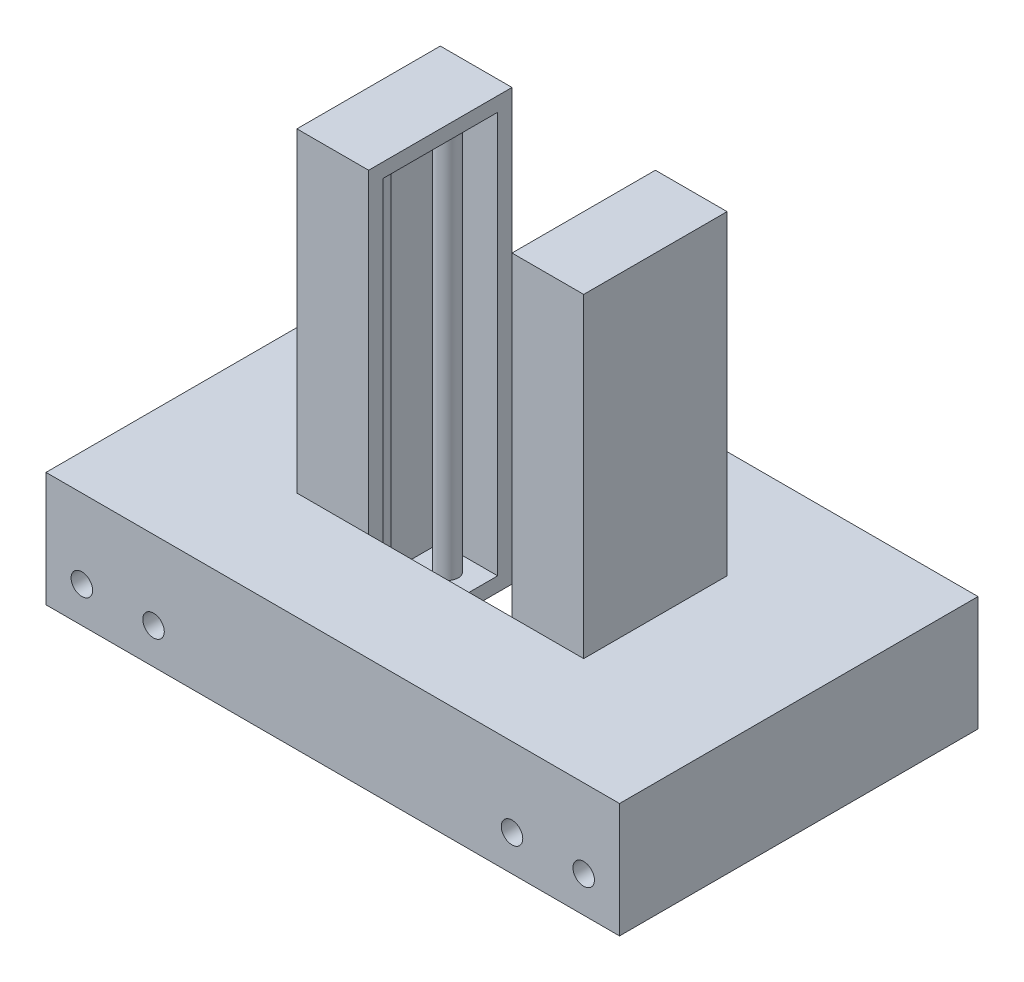
SolidWorks part; units mm, degrees
ref_plane "Front Plane" through (0, 0, 0) normal (0, 0, 1) x (1, 0, 0)
ref_plane "Top Plane" through (0, 0, 0) normal (0, 1, 0) x (1, 0, 0)
ref_plane "Right Plane" through (0, 0, 0) normal (1, 0, 0) x (0, 0, -1)
sketch "Sketch1" plane through (0, 0, 0) normal (0, 1, 0) x (1, 0, 0)
  line L1 (0, 0) -> (-400, 0)
  line L2 (0, 0) -> (0, 250)
  line L3 (0, 250) -> (-400, 250)
  line L4 (-400, 0) -> (-400, 250)
  dimension "D1" = 400
  dimension "D2" = 250
extrude "Boss-Extrude1" add sketch "Sketch1" along normal blind 80
sketch "Sketch2" plane through (0, 0, 0) normal (0, 0, 1) x (1, 0, 0)
  line L0 (-400, 0) -> (0, 0) construction
  line L1 (0, 80) -> (0, 0) construction
  line L2 (-400, 80) -> (-400, 0) construction
  circle A0 centre (-375, 25) radius 7.5
  circle A1 centre (-325, 25) radius 7.5
  circle A2 centre (-75, 25) radius 7.5
  circle A3 centre (-25, 25) radius 7.5
  dimension "D1" = 15
  dimension "D2" = 15
  dimension "D3" = 15
  dimension "D4" = 15
  dimension "D5" = 25
  dimension "D6" = 25
  dimension "D7" = 25
  dimension "D8" = 50
  dimension "D9" = 25
  dimension "D10" = 50
  dimension "D11" = 25
  dimension "D12" = 25
extrude "Cut-Extrude1" cut sketch "Sketch2" against normal through all
sketch "Sketch5" plane through (0, 80, 0) normal (0, 1, 0) x (1, 0, 0)
  line L0 (0, 250) -> (-400, 250) construction
  line L1 (-300, 175) -> (-100, 175)
  line L2 (-300, 175) -> (-300, 75)
  line L3 (-300, 75) -> (-100, 75)
  line L4 (-100, 175) -> (-100, 75)
  line L6 (0, 0) -> (0, 250) construction
  dimension "D1" = 200
  dimension "D2" = 100
  dimension "D3" = 75
  dimension "D4" = 100
extrude "Cut-Extrude2" cut sketch "Sketch5" against normal through all
sketch "Sketch8" plane through (-300, 0, 0) normal (1, 0, 0) x (0, 0, -1)
  line L0 (0, 0) -> (250, 0) construction
  line L1 (75, 0) -> (175, 0)
  line L2 (75, 0) -> (75, 300)
  line L3 (75, 300) -> (175, 300)
  line L4 (175, 0) -> (175, 300)
  line L5 (75, 0) -> (75, 80) construction
  line L6 (175, 0) -> (175, 80) construction
  dimension "D1" = 0
  dimension "D2" = 0
  dimension "D3" = 300
extrude "Boss-Extrude2" add sketch "Sketch8" along normal blind 50
sketch "Sketch9" plane through (-250, 0, 0) normal (1, 0, 0) x (0, 0, -1)
  line L0 (175, 80) -> (175, 300) construction
  line L1 (85, 290) -> (165, 290)
  line L2 (85, 290) -> (85, 10)
  line L3 (85, 10) -> (165, 10)
  line L4 (165, 290) -> (165, 10)
  line L5 (75, 300) -> (75, 80) construction
  line L6 (175, 300) -> (75, 300) construction
  line L7 (75, 0) -> (175, 0) construction
  dimension "D1" = 10
  dimension "D2" = 10
  dimension "D3" = 10
  dimension "D4" = 10
extrude "Cut-Extrude3" cut sketch "Sketch9" against normal blind 40
ref_plane "Plane2" through (-200, 0, 0) normal (-1, 0, 0) x (0, 0, 1)
mirror "Mirror1" about plane through (-200, 0, 0) normal (-1, 0, 0) of "Cut-Extrude3", "Boss-Extrude2"
sketch "Sketch10" plane through (0, 10, 0) normal (0, 1, 0) x (1, 0, 0)
  line L0 (-250, 175) -> (-300, 175) construction
  line L1 (-250, 75) -> (-300, 75) construction
  line L2 (-250, 85) -> (-250, 165) construction
  circle A0 centre (-270, 150) radius 7.5
  circle A1 centre (-270, 100) radius 7.5
  dimension "D1" = 15
  dimension "D2" = 15
  dimension "D3" = 25
  dimension "D4" = 25
  dimension "D5" = 20
  dimension "D6" = 20
extrude "Boss-Extrude3" add sketch "Sketch10" along normal blind 280
mirror "Mirror2" about plane through (-200, 0, 0) normal (-1, 0, 0) of "Boss-Extrude3"
